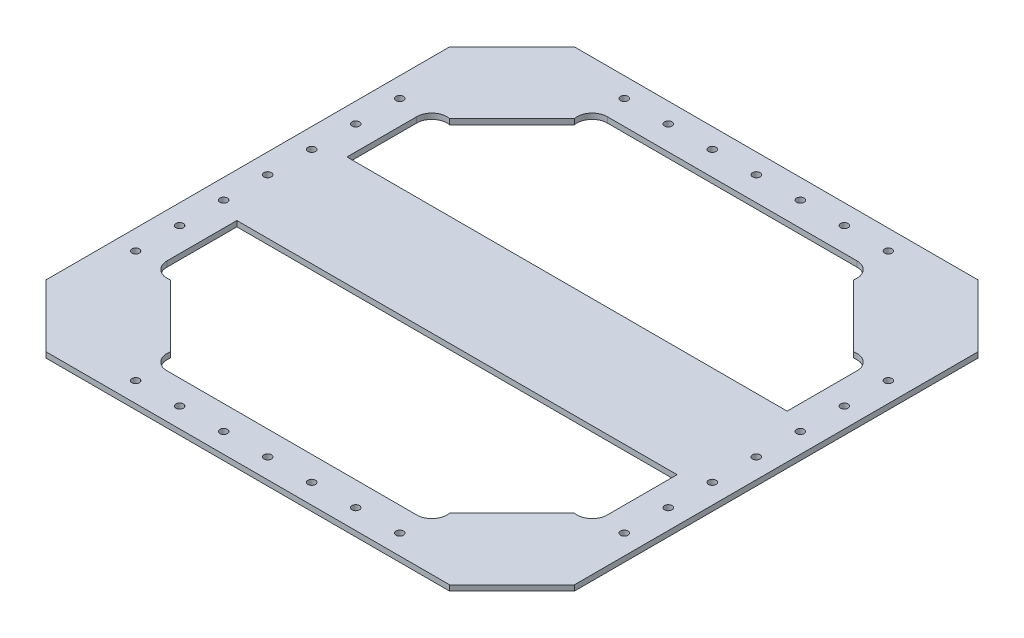
SolidWorks part; units mm, degrees
ref_plane "Front Plane" through (0, 0, 0) normal (0, 0, 1) x (1, 0, 0)
ref_plane "Top Plane" through (0, 0, 0) normal (0, 1, 0) x (1, 0, 0)
ref_plane "Right Plane" through (0, 0, 0) normal (1, 0, 0) x (0, 0, -1)
sketch "Sketch1" plane through (0, 0, 0) normal (0, 1, 0) x (1, 0, 0)
  line L0 (-152.4, 68.2596) -> (-116.479, 104.1807)
  line L1 (-116.479, 104.1807) -> (116.479, 104.1807)
  line L2 (-152.4, 68.2596) -> (-152.4, -164.6983)
  line L3 (152.4, 68.2596) -> (152.4, -164.6983)
  line L4 (152.4, 68.2596) -> (116.479, 104.1807)
  line L5 (0, 104.1807) -> (0, -200.6193) construction
  line L6 (-152.4, -48.2193) -> (152.4, -48.2193) construction
  line L7 (152.4, -164.6983) -> (116.479, -200.6193)
  line L8 (-116.479, -200.6193) -> (116.479, -200.6193)
  line L9 (-152.4, -164.6983) -> (-116.479, -200.6193)
  point P9 (0, -48.2193)
  point P11 (0, -48.2193)
  dimension "D3" = 50.8
  dimension "D4" = 135
extrude "Boss-Extrude1" add sketch "Sketch1" along normal blind 3.175
sketch "Sketch2" plane through (0, 3.175, 0) normal (0, 1, 0) x (1, 0, 0)
  line L0 (-152.4, -48.2193) -> (199.0625, -48.2193) construction
  line L1 (-152.4, 68.2596) -> (-152.4, -164.6983) construction
  line L2 (-91.079, 78.7807) -> (91.079, 78.7807)
  line L4 (82.443, -16.4693) -> (-74.315, -16.4693)
  line L6 (-116.479, 104.1807) -> (-91.079, 78.7807) construction
  line L7 (116.479, 104.1807) -> (91.079, 78.7807) construction
  line L8 (116.479, 104.1807) -> (-116.479, 104.1807) construction
  line L9 (-74.315, -16.4693) -> (-127, -16.4693)
  line L10 (-127, -16.4693) -> (-127, 42.8596)
  line L11 (-127, 42.8596) -> (-91.079, 78.7807)
  line L12 (82.443, -16.4693) -> (127, -16.4693)
  line L13 (127, -16.4693) -> (127, 42.8596)
  line L14 (127, 42.8596) -> (91.079, 78.7807)
  line L16 (127, -139.2983) -> (91.079, -175.2193)
  line L17 (127, -79.9693) -> (127, -139.2983)
  line L18 (82.443, -79.9693) -> (127, -79.9693)
  line L19 (-127, -139.2983) -> (-91.079, -175.2193)
  line L20 (-127, -79.9693) -> (-127, -139.2983)
  line L21 (-74.315, -79.9693) -> (-127, -79.9693)
  line L23 (82.443, -79.9693) -> (-74.315, -79.9693)
  line L25 (-91.079, -175.2193) -> (91.079, -175.2193)
  dimension "D1" = 135
  dimension "D2" = 135
  dimension "D3" = 25.4
  dimension "D4" = 90
  dimension "D5" = 90
  dimension "D6" = 50.8
  dimension "D7" = 50.8
  dimension "D8" = 31.75
  dimension "D9" = 25.4
extrude "Cut-Extrude1" cut sketch "Sketch2" against normal through all
sketch "Sketch4" plane through (0, 3.175, 0) normal (0, 1, 0) x (1, 0, 0)
  line L0 (-152.4, -48.2193) -> (171.6111, -48.2193) construction
  line L1 (-152.4, 68.2596) -> (-152.4, -164.6983) construction
  line L2 (116.479, 104.1807) -> (-116.479, 104.1807) construction
  line L4 (152.4, -164.6983) -> (152.4, 68.2596) construction
  circle A0 centre (0, 92.7507) radius 2.159
  circle A1 centre (-50.8, 92.7507) radius 2.159
  circle A2 centre (50.8, 92.7507) radius 2.159
  circle A3 centre (-25.4, 92.7507) radius 2.159
  circle A4 centre (25.4, 92.7507) radius 2.159
  circle A5 centre (-140.97, -48.2193) radius 2.159
  circle A6 centre (-140.97, -22.8193) radius 2.159
  circle A7 centre (-140.97, 2.5807) radius 2.159
  circle A8 centre (140.97, -48.2193) radius 2.159
  circle A9 centre (140.97, -22.8193) radius 2.159
  circle A10 centre (140.97, 2.5807) radius 2.159
  circle A11 centre (140.97, -99.0193) radius 2.159
  circle A12 centre (140.97, -73.6193) radius 2.159
  circle A13 centre (-140.97, -99.0193) radius 2.159
  circle A14 centre (-140.97, -73.6193) radius 2.159
  circle A15 centre (25.4, -189.1893) radius 2.159
  circle A16 centre (-25.4, -189.1893) radius 2.159
  circle A17 centre (50.8, -189.1893) radius 2.159
  circle A18 centre (-50.8, -189.1893) radius 2.159
  circle A19 centre (0, -189.1893) radius 2.159
  circle A20 centre (-76.2, 92.7507) radius 2.159
  circle A21 centre (76.2, 92.7507) radius 2.159
  circle A22 centre (-140.97, 27.9807) radius 2.159
  circle A23 centre (140.97, 27.9807) radius 2.159
  circle A24 centre (140.97, -124.4193) radius 2.159
  circle A25 centre (76.2, -189.1893) radius 2.159
  circle A26 centre (-76.2, -189.1893) radius 2.159
  circle A27 centre (-140.97, -124.4193) radius 2.159
  point P48 (0, 104.1807)
  dimension "D1" = 4.318
  dimension "D2" = 4.318
  dimension "D3" = 4.318
  dimension "D4" = 4.318
  dimension "D5" = 4.318
  dimension "D6" = 4.318
  dimension "D7" = 4.318
  dimension "D8" = 4.318
  dimension "D9" = 4.318
  dimension "D10" = 4.318
  dimension "D11" = 4.318
  dimension "D23" = 4.318
  dimension "D24" = 4.318
  dimension "D27" = 4.318
  dimension "D28" = 4.318
  dimension "D12" = 25.4
  dimension "D13" = 25.4
  dimension "D14" = 25.4
  dimension "D15" = 25.4
  dimension "D16" = 25.4
  dimension "D17" = 25.4
  dimension "D18" = 25.4
  dimension "D19" = 25.4
  dimension "D20" = 11.43
  dimension "D21" = 11.43
  dimension "D22" = 11.43
  dimension "D25" = 25.4
  dimension "D26" = 25.4
  dimension "D29" = 25.4
  dimension "D30" = 25.4
sketch "Sketch5" plane through (0, 3.175, 0) normal (0, 1, 0) x (1, 0, 0)
  line L0 (-116.479, 32.3386) -> (-80.558, 68.2596)
  line L1 (0, 78.7807) -> (0, -138.0704) construction
  line L3 (-152.4, 68.2596) -> (-152.4, 11.1096)
  line L4 (-127, 42.8596) -> (-127, -16.4693) construction
  line L5 (91.079, 78.7807) -> (-91.079, 78.7807) construction
  line L6 (-116.479, 104.1807) -> (-59.329, 104.1807)
  line L7 (116.479, 104.1807) -> (-116.479, 104.1807) construction
  line L8 (-59.329, 104.1807) -> (-59.329, 78.7807)
  line L9 (-152.4, 68.2596) -> (-116.479, 104.1807)
  line L10 (-152.4, 68.2596) -> (-152.4, -164.6983) construction
  line L12 (-152.4, 11.1096) -> (-127, 11.1096)
  line L13 (-59.329, 78.7807) -> (-72.029, 78.7807)
  line L14 (127, 11.1096) -> (127, 23.8096)
  line L15 (152.4, -48.2193) -> (-208.2375, -48.2193) construction
  line L16 (152.4, -164.6983) -> (152.4, 68.2596) construction
  line L17 (59.329, 78.7807) -> (72.029, 78.7807)
  line L18 (-127, 11.1096) -> (-127, 23.8096)
  line L19 (152.4, 11.1096) -> (127, 11.1096)
  line L20 (152.4, 68.2596) -> (116.479, 104.1807)
  line L21 (59.329, 104.1807) -> (59.329, 78.7807)
  line L22 (116.479, 104.1807) -> (59.329, 104.1807)
  line L24 (152.4, 68.2596) -> (152.4, 11.1096)
  line L25 (116.479, 32.3386) -> (80.558, 68.2596)
  line L26 (116.479, -128.7773) -> (80.558, -164.6983)
  line L27 (152.4, -164.6983) -> (152.4, -107.5483)
  line L28 (116.479, -200.6193) -> (59.329, -200.6193)
  line L29 (59.329, -200.6193) -> (59.329, -175.2193)
  line L30 (152.4, -164.6983) -> (116.479, -200.6193)
  line L31 (152.4, -107.5483) -> (127, -107.5483)
  line L32 (-127, -107.5483) -> (-127, -120.2483)
  line L33 (59.329, -175.2193) -> (72.029, -175.2193)
  line L34 (127, -107.5483) -> (127, -120.2483)
  line L35 (-59.329, -175.2193) -> (-72.029, -175.2193)
  line L36 (-152.4, -107.5483) -> (-127, -107.5483)
  line L37 (-152.4, -164.6983) -> (-116.479, -200.6193)
  line L38 (-59.329, -200.6193) -> (-59.329, -175.2193)
  line L39 (-116.479, -200.6193) -> (-59.329, -200.6193)
  line L40 (-152.4, -164.6983) -> (-152.4, -107.5483)
  line L41 (-116.479, -128.7773) -> (-80.558, -164.6983)
  arc A0 (-72.029, 78.7807) -> (-80.558, 68.2596) centre (-72.029, 70.0631) ccw
  arc A1 (-127, 23.8096) -> (-116.479, 32.3386) centre (-118.2824, 23.8096) cw
  arc A2 (127, 23.8096) -> (116.479, 32.3386) centre (118.2824, 23.8096) ccw
  arc A3 (72.029, 78.7807) -> (80.558, 68.2596) centre (72.029, 70.0631) cw
  arc A4 (72.029, -175.2193) -> (80.558, -164.6983) centre (72.029, -166.5018) ccw
  arc A5 (127, -120.2483) -> (116.479, -128.7773) centre (118.2824, -120.2483) cw
  arc A6 (-127, -120.2483) -> (-116.479, -128.7773) centre (-118.2824, -120.2483) ccw
  arc A7 (-72.029, -175.2193) -> (-80.558, -164.6983) centre (-72.029, -166.5018) cw
  dimension "D3" = 12.7
  dimension "D1" = 50.8
  dimension "D2" = 50.8
  dimension "D4" = 12.7
  dimension "D5" = 57.15
  dimension "D6" = 57.15
extrude "Boss-Extrude2" add sketch "Sketch5" against normal blind 3.175
extrude "Cut-Extrude2" cut sketch "Sketch4" against normal through all
